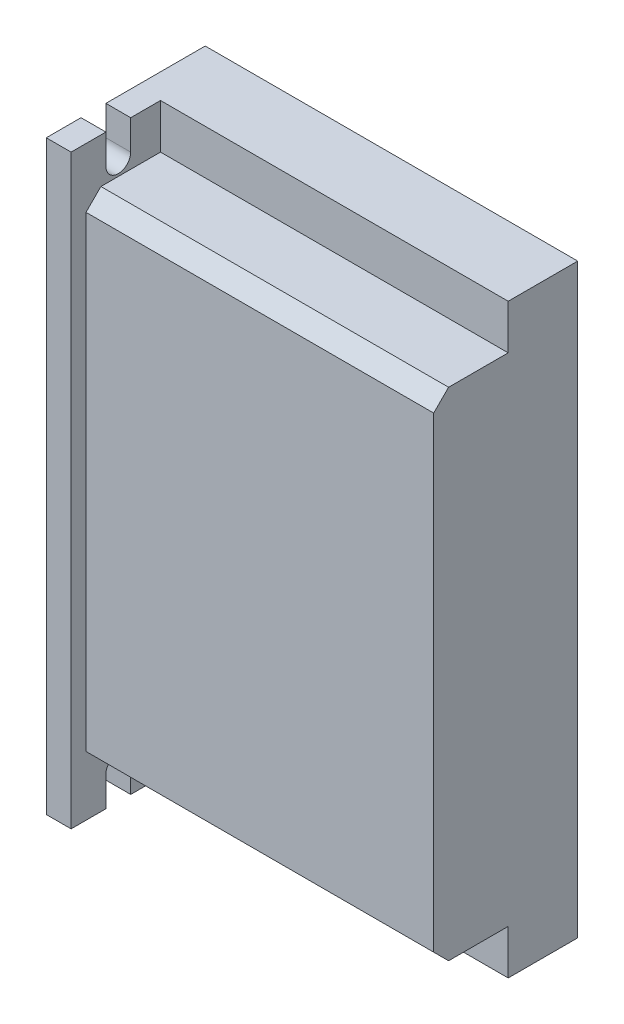
SolidWorks part; units mm, degrees
ref_plane "Спереди" through (0, 0, 0) normal (0, 0, 1) x (1, 0, 0)
ref_plane "Сверху" through (0, 0, 0) normal (0, 1, 0) x (1, 0, 0)
ref_plane "Справа" through (0, 0, 0) normal (1, 0, 0) x (0, 0, -1)
sketch "Эскиз1" plane through (0, 0, 0) normal (0, 0, 1) x (1, 0, 0)
  line L1 (0, 0) -> (75, 0)
  line L2 (0, 0) -> (0, 100)
  line L3 (0, 100) -> (75, 100)
  line L4 (75, 0) -> (75, 100)
  dimension "D1" = 75
  dimension "D2" = 100
extrude "Бобышка-Вытянуть1" add sketch "Эскиз1" along normal blind 18
sketch "Эскиз2" plane through (0, 0, 0) normal (0, 0, -1) x (-1, 0, 0)
  line L0 (-75, 100) -> (0, 100) construction
  line L1 (-75, 109) -> (0, 109)
  line L2 (-75, 109) -> (-75, -9)
  line L3 (-75, -9) -> (0, -9)
  line L4 (0, 109) -> (0, -9)
  dimension "D1" = 9
  dimension "D2" = 118
extrude "Бобышка-Вытянуть2" add sketch "Эскиз2" along normal blind 14
sketch "Эскиз3" plane through (0, 0, 0) normal (-1, 0, 0) x (0, 0, 1)
  line L1 (0, 109) -> (18, 109)
  line L2 (0, 109) -> (0, -9)
  line L3 (0, -9) -> (18, -9)
  line L4 (18, 109) -> (18, -9)
extrude "Бобышка-Вытянуть3" add sketch "Эскиз3" against normal blind 5
sketch "Эскиз4" plane through (0, 0, 0) normal (-1, 0, 0) x (0, 0, 1)
  line L0 (8.5, 114.7341) -> (8.5, 103) construction
  line L1 (11, 114.7341) -> (11, 103)
  line L2 (6, 114.7341) -> (6, 103)
  line L3 (18, 100) -> (0, 100) construction
  line L4 (18, 109) -> (18, -9) construction
  line L5 (-14, 50) -> (18, 50) construction
  line L6 (-14, -9) -> (-14, 109) construction
  line L7 (8.5, -14.7341) -> (8.5, -3) construction
  line L8 (11, -14.7341) -> (11, -3)
  line L9 (6, -14.7341) -> (6, -3)
  arc A0 (11, 114.7341) -> (6, 114.7341) centre (8.5, 114.7341) ccw
  arc A1 (6, 103) -> (11, 103) centre (8.5, 103) ccw
  arc A2 (11, -14.7341) -> (6, -14.7341) centre (8.5, -14.7341) cw
  arc A3 (6, -3) -> (11, -3) centre (8.5, -3) cw
  point P2 (8.5, 108.867)
  point P17 (8.5, -8.867)
  dimension "D1" = 5
  dimension "D2" = 3
  dimension "D3" = 9.5
extrude "Вырез-Вытянуть1" cut sketch "Эскиз4" against normal through all
sketch "Эскиз5" plane through (0, 0, 18) normal (0, 0, 1) x (1, 0, 0)
  line L1 (5, 100) -> (75, 100)
  line L2 (5, 100) -> (5, 0)
  line L3 (5, 0) -> (75, 0)
  line L4 (75, 100) -> (75, 0)
extrude "Вырез-Вытянуть2" cut sketch "Эскиз5" against normal blind 3
chamfer "Фаска1" distance 3 angle 45 2 edges at (40, 0, 15) (40, 100, 15)
